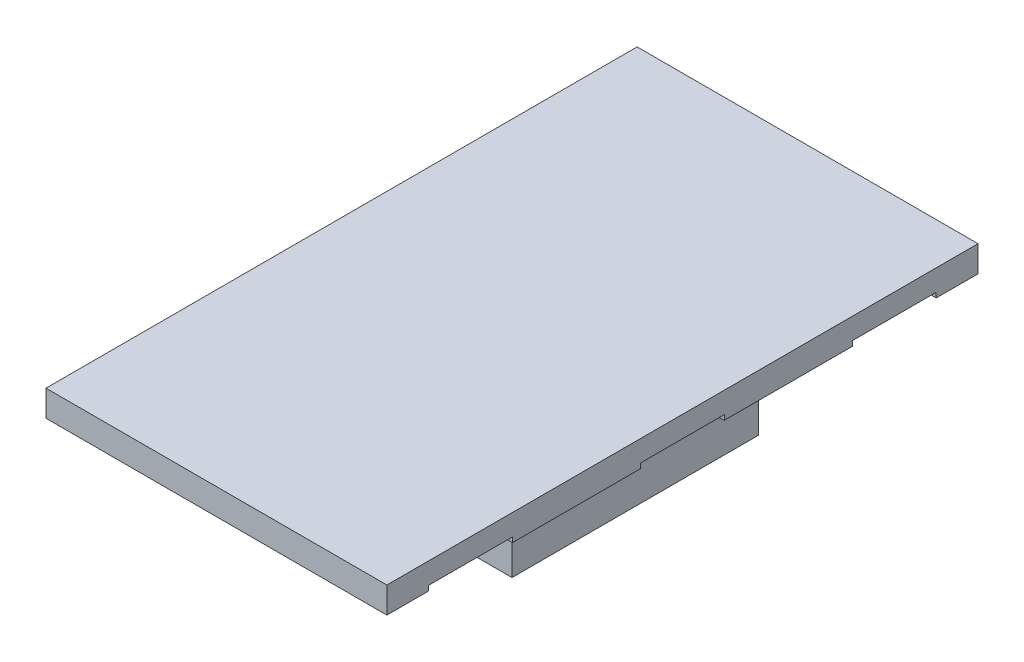
SolidWorks part; units mm, degrees
ref_plane "Спереди" through (0, 0, 0) normal (0, 0, 1) x (1, 0, 0)
ref_plane "Сверху" through (0, 0, 0) normal (0, 1, 0) x (1, 0, 0)
ref_plane "Справа" through (0, 0, 0) normal (1, 0, 0) x (0, 0, -1)
sketch "Sketch1" plane through (0, 0, 0) normal (0, 1, 0) x (1, 0, 0)
  line L1 (3.46, -6) -> (-3.46, -6)
  line L2 (3.46, -6) -> (3.46, 6)
  line L3 (3.46, 6) -> (-3.46, 6)
  line L4 (-3.46, -6) -> (-3.46, 6)
  line L5 (3.46, -6) -> (-3.46, 6) construction
  line L6 (3.46, 6) -> (-3.46, -6) construction
  point P0 (0, 0)
  dimension "D1" = 12
  dimension "D2" = 6.92
extrude "Boss-Extrude1" add sketch "Sketch1" along normal blind 0.53
sketch "Sketch2" plane through (0, 0, 0) normal (0, -1, 0) x (1, 0, 0)
  line L1 (2.5, 2.5) -> (-2.5, 2.5)
  line L2 (2.5, 2.5) -> (2.5, -2.5)
  line L3 (2.5, -2.5) -> (-2.5, -2.5)
  line L4 (-2.5, 2.5) -> (-2.5, -2.5)
  line L5 (2.5, 2.5) -> (-2.5, -2.5) construction
  line L6 (2.5, -2.5) -> (-2.5, 2.5) construction
  point P0 (0, 0)
  dimension "D1" = 5
  dimension "D2" = 5
extrude "Boss-Extrude2" add sketch "Sketch2" along normal blind 1.57
sketch "Sketch3" plane through (0, -1.57, 0) normal (0, -1, 0) x (1, 0, 0)
  circle A0 centre (0, 0) radius 2
extrude "Cut-Extrude1" cut sketch "Sketch3" against normal blind 0.2
chamfer "Chamfer1" distance 0.1 angle 45 1 edges at (0, -1.57, -2)
sketch "Sketch4" plane through (0, 0, 0) normal (0, -1, 0) x (1, 0, 0)
  line L0 (0, 6.476) -> (0, -6.9083) construction
  line L5 (3.46, 0.85) -> (3.46, -0.85)
  line L6 (3.46, 5.1515) -> (2.351, 5.1515)
  line L7 (2.351, 3.4515) -> (3.46, 3.4515)
  line L8 (3.46, -6) -> (-3.46, -6) construction
  line L9 (3.46, 3.4515) -> (3.46, 5.1515)
  line L11 (3.46, -5.1515) -> (2.351, -5.1515)
  line L13 (-2.351, -3.4515) -> (-3.46, -3.4515)
  line L14 (-3.46, -3.4515) -> (-3.46, -5.1515)
  line L15 (-3.46, -5.1515) -> (-2.351, -5.1515)
  line L16 (-9.0262, 0) -> (8.7663, 0) construction
  line L17 (-3.46, 3.4515) -> (-3.46, 5.1515)
  line L18 (-2.351, 3.4515) -> (-3.46, 3.4515)
  line L19 (-3.46, 5.1515) -> (-2.351, 5.1515)
  line L20 (-3.46, -6) -> (-3.46, 6) construction
  line L21 (-3.46, 0.85) -> (-3.46, -0.85)
  line L22 (3.46, -3.4515) -> (3.46, -5.1515)
  line L23 (2.351, -3.4515) -> (3.46, -3.4515)
  arc A2 (-2.351, -3.4515) -> (-2.351, -5.1515) centre (-2.351, -4.3015) cw
  arc A4 (-2.351, 3.4515) -> (-2.351, 5.1515) centre (-2.351, 4.3015) ccw
  arc A5 (-3.46, 0.85) -> (-3.46, -0.85) centre (-3.46, 0) cw
  arc A6 (3.46, 0.85) -> (3.46, -0.85) centre (3.46, 0) ccw
  arc A7 (2.351, 3.4515) -> (2.351, 5.1515) centre (2.351, 4.3015) cw
  arc A8 (2.351, -3.4515) -> (2.351, -5.1515) centre (2.351, -4.3015) ccw
  point P14 (-2.5468, -6)
  point P38 (2.5468, -6)
  dimension "D5" = 0.85
  dimension "D6" = 0.85
  dimension "D4" = 1.7
sketch "Sketch6" plane through (0, 0, 0) normal (0, -1, 0) x (1, 0, 0)
  line L1 (-1, -4.85) -> (1, -4.85)
  line L2 (-1, -4.85) -> (-1, -3.65)
  line L3 (-1, -3.65) -> (1, -3.65)
  line L4 (1, -4.85) -> (1, -3.65)
extrude "Boss-Extrude3" add sketch "Sketch6" along normal blind 0.45
extrude "Cut-Extrude2" cut sketch "Sketch4" against normal blind 0.1
